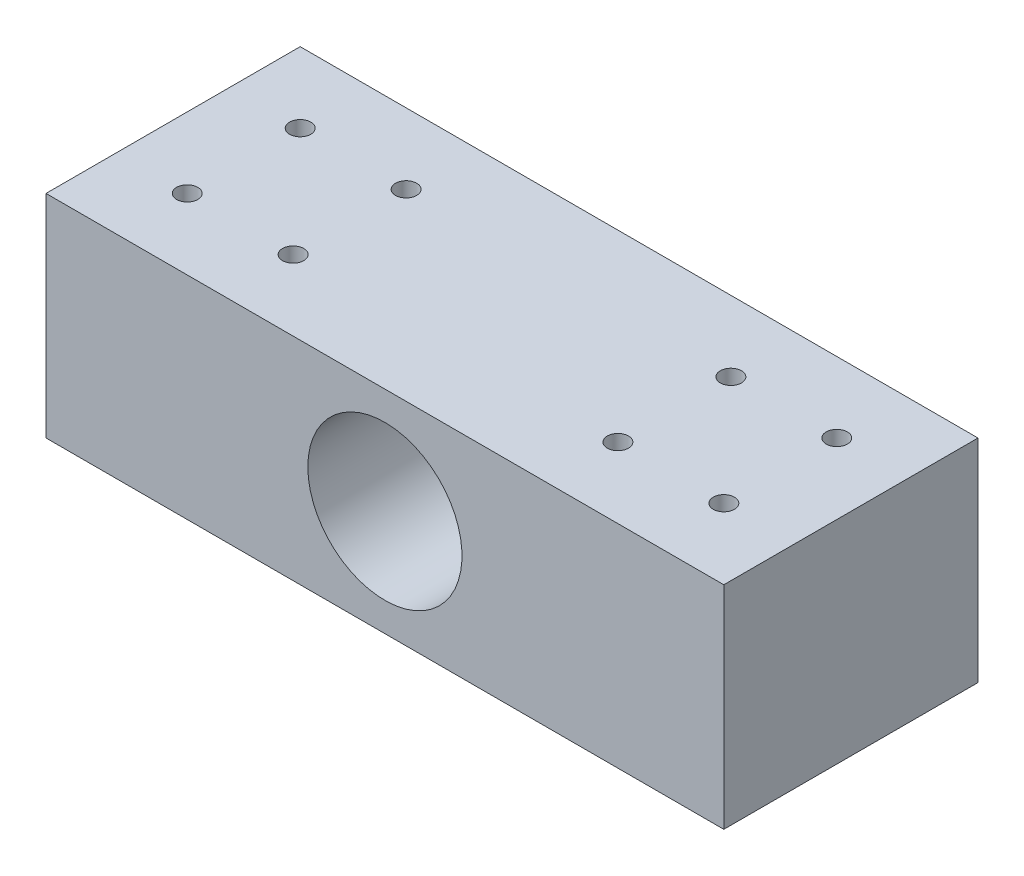
SolidWorks part; units mm, degrees
ref_plane "前视基准面" through (0, 0, 0) normal (0, 0, 1) x (1, 0, 0)
ref_plane "上视基准面" through (0, 0, 0) normal (0, 1, 0) x (1, 0, 0)
ref_plane "右视基准面" through (0, 0, 0) normal (1, 0, 0) x (0, 0, -1)
sketch "草图1" plane through (0, 0, 0) normal (0, 1, 0) x (1, 0, 0)
  line L0 (48, -962.5843) -> (48, 49037.4157) construction
  line L1 (0, 0) -> (96, 0)
  line L2 (0, 0) -> (0, 36)
  line L3 (0, 36) -> (96, 36)
  line L4 (96, 0) -> (96, 36)
  line L5 (10, -972.5843) -> (10, 49027.4157) construction
  line L6 (25, -972.5843) -> (25, 49027.4157) construction
  circle A0 centre (10, 26) radius 1.5
  circle A1 centre (25, 26) radius 1.5
  circle A2 centre (25, 10) radius 1.5
  circle A3 centre (10, 10) radius 1.5
  circle A4 centre (86, 26) radius 1.5
  circle A5 centre (86, 10) radius 1.5
  circle A6 centre (71, 10) radius 1.5
  circle A7 centre (71, 26) radius 1.5
  point P14 (0, 0)
  point P16 (48, 36)
  point P21 (0, 0)
  point P30 (25, 10)
  point P31 (25, 26)
  point P32 (71, 10)
  dimension "D1" = 15
  dimension "D5" = 3
  dimension "D6" = 3
  dimension "D7" = 3
  dimension "D8" = 3
  dimension "D2" = 16
  dimension "D3" = 16
  dimension "D4" = 15
  dimension "D9" = 10
  dimension "D10" = 10
  dimension "D11" = 10
  dimension "D12" = 23
extrude "凸台-拉伸1" add sketch "草图1" along normal blind 30
sketch "草图2" plane through (0, 0, -36) normal (0, 0, -1) x (-1, 0, 0)
  line L0 (-1000.9607, 15) -> (48999.0393, 15) construction
  line L1 (0, 30) -> (0, 0) construction
  line L2 (-48, -970) -> (-48, 49030) construction
  line L4 (-96, 30) -> (0, 30) construction
  circle A0 centre (-48, 15) radius 10.9175
  point P7 (0, 15)
  point P8 (-48, 15)
  point P12 (-48, 30)
  dimension "D1" = 21.835
extrude "切除-拉伸1" cut sketch "草图2" against normal through all both and the other way through all
